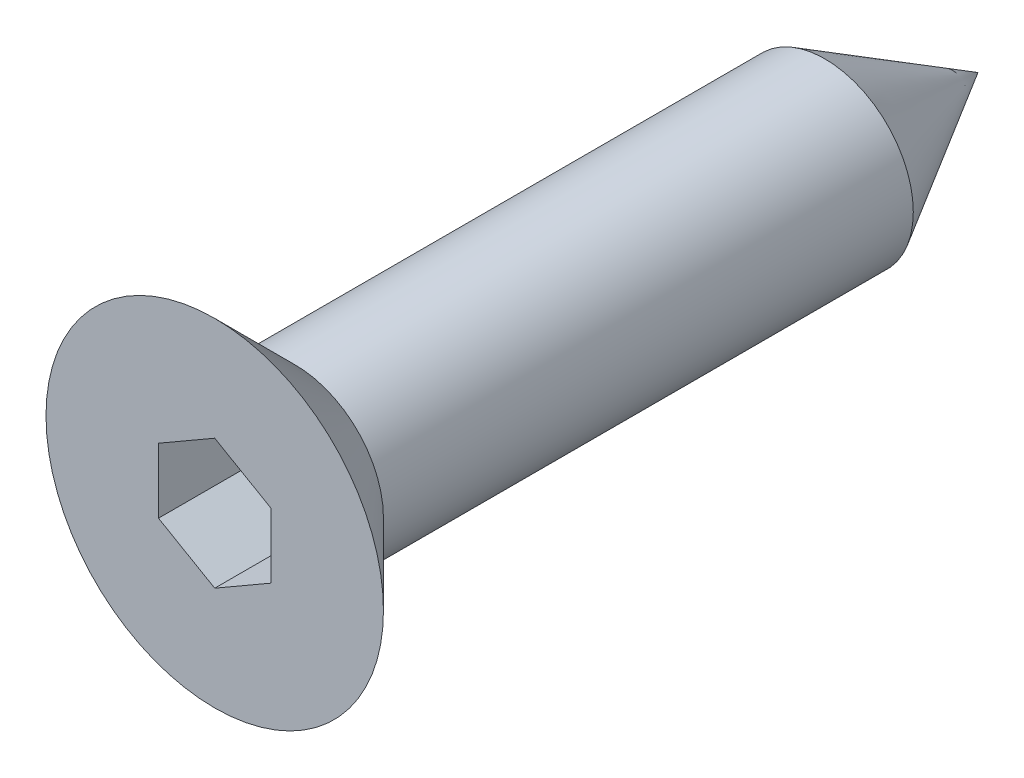
SolidWorks part; units mm, degrees
ref_plane "Plan de face" through (0, 0, 0) normal (0, 0, 1) x (1, 0, 0)
ref_plane "Plan de dessus" through (0, 0, 0) normal (0, 1, 0) x (1, 0, 0)
ref_plane "Plan de droite" through (0, 0, 0) normal (1, 0, 0) x (0, 0, -1)
sketch "Esquisse1" plane through (0, 0, 0) normal (1, 0, 0) x (0, 0, -1)
  line L0 (-1.6035, 0) -> (7.1529, 0) construction
  line L1 (0, 5.0438) -> (0, -4.594) construction
  line L2 (0, 2.1) -> (1, 1.1)
  line L3 (1, 1.1) -> (1, 0)
  line L5 (0, 2.1) -> (8.0645, -5.9645) construction
  line L6 (-1.0465, 1.1) -> (4.1553, 1.1) construction
  line L7 (1, 0) -> (0, 0)
  line L9 (0, 2.1) -> (0, 0)
  dimension "D1" = 45
revolve "Révolution2" add sketch "Esquisse1" angle 360 about L0
sketch "Esquisse3" plane through (0, 0, 0) normal (0, 0, 1) x (1, 0, 0)
  circle A0 centre (0, 0) radius 1.1
extrude "Extrusion1" add sketch "Esquisse3" against normal blind 9.5
sketch "Esquisse2" plane through (0, 0, 0) normal (0, 0, 1) x (1, 0, 0)
  line L1 (0, 0.8083) -> (-0.7, 0.4041)
  line L2 (-0.7, 0.4041) -> (-0.7, -0.4041)
  line L3 (-0.7, -0.4041) -> (0, -0.8083)
  line L4 (0, -0.8083) -> (0.7, -0.4041)
  line L5 (0.7, -0.4041) -> (0.7, 0.4041)
  line L6 (0.7, 0.4041) -> (0, 0.8083)
  circle A0 centre (0, 0) radius 1.8 construction
  circle A1 centre (0, 0) radius 0.7 construction
extrude "Enlèv. mat.-Extru.2" cut sketch "Esquisse2" against normal blind 1.5
chamfer "Chanfrein1" distance 1.1 angle 60 1 edges at (1.1, 0, -9.5)
